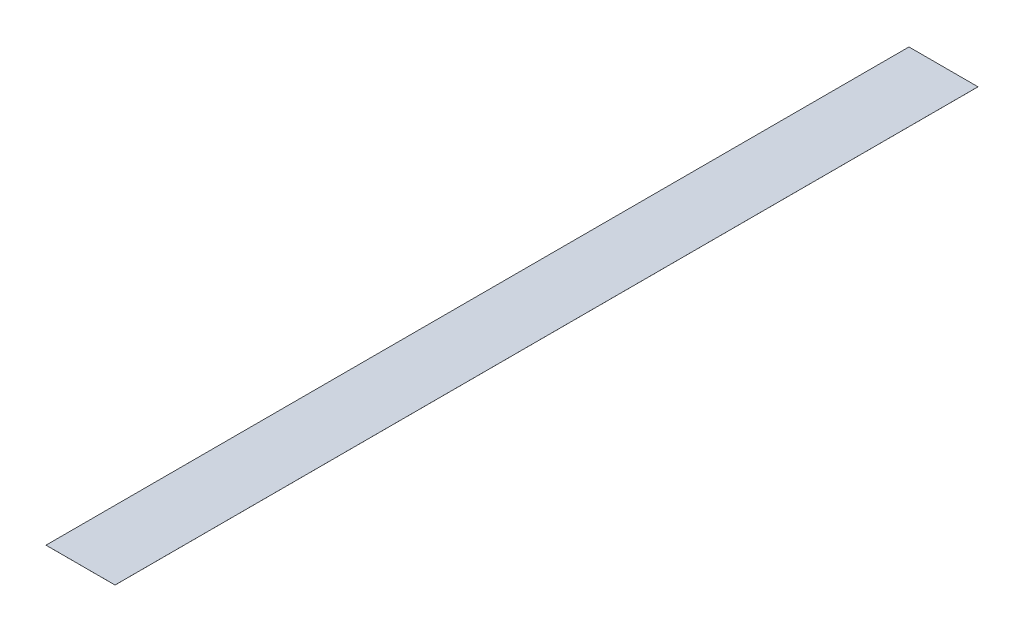
SolidWorks part; units mm, degrees
ref_plane "Plano frontal" through (0, 0, 0) normal (0, 0, 1) x (1, 0, 0)
ref_plane "Plano superior" through (0, 0, 0) normal (0, 1, 0) x (1, 0, 0)
ref_plane "Plano direito" through (0, 0, 0) normal (1, 0, 0) x (0, 0, -1)
sketch "Esboço1" plane through (0, 0, 0) normal (0, 1, 0) x (1, 0, 0)
  line L0 (-1093, 595.536) -> (-1073, 595.536)
  line L1 (0, 0) -> (18.9344, 0)
  line L2 (0, 0) -> (0, 766.8662)
  line L3 (0, 766.8662) -> (18.9344, 766.8662)
  line L4 (18.9344, 0) -> (18.9344, 766.8662)
  line L5 (-381.6968, 766.8662) -> (-362.7624, 766.8662)
  line L6 (-381.6968, 766.8662) -> (-381.6968, 345.536)
  line L7 (-381.6968, 345.536) -> (-362.7624, 345.536)
  line L8 (-362.7624, 766.8662) -> (-362.7624, 345.536)
  line L9 (-858.9344, 645.536) -> (-840, 645.536)
  line L10 (-858.9344, 645.536) -> (-858.9344, 345.536)
  line L11 (-858.9344, 345.536) -> (-840, 345.536)
  line L12 (-840, 645.536) -> (-840, 345.536)
  line L13 (-853.5858, 925.2213) -> (-1253.5858, 925.2213)
  line L14 (-853.5858, 925.2213) -> (-853.5858, 945.2213)
  line L15 (-853.5858, 945.2213) -> (-1253.5858, 945.2213)
  line L16 (-1253.5858, 925.2213) -> (-1253.5858, 945.2213)
  line L17 (-1093, 595.536) -> (-1093, 195.536)
  line L18 (-1093, 195.536) -> (-1073, 195.536)
  line L19 (-1073, 595.536) -> (-1073, 195.536)
  line L21 (-858.9344, 427.7897) -> (-1250.0103, 427.7897)
  line L23 (-858.9344, 407.7897) -> (-1250.0103, 407.7897)
  line L24 (-1250.0103, 427.7897) -> (-1250.0103, 407.7897)
  line L33 (-1439.6613, 239.7512) -> (-1560.0448, 239.7512)
  line L34 (-1439.6613, 239.7512) -> (-1439.6613, 219.7512)
  line L35 (-1439.6613, 219.7512) -> (-1560.0448, 219.7512)
  line L36 (-1560.0448, 239.7512) -> (-1560.0448, 219.7512)
  line L37 (-1627.2015, 576.144) -> (-1607.2015, 576.144)
  line L38 (-1627.2015, 576.144) -> (-1627.2015, 317.0654)
  line L39 (-1627.2015, 317.0654) -> (-1607.2015, 317.0654)
  line L40 (-1607.2015, 576.144) -> (-1607.2015, 317.0654)
  line L41 (-1627.2015, 769.6927) -> (-1607.2015, 769.6927)
  line L42 (-1627.2015, 769.6927) -> (-1627.2015, 1019.6927)
  line L43 (-1627.2015, 1019.6927) -> (-1607.2015, 1019.6927)
  line L44 (-1607.2015, 769.6927) -> (-1607.2015, 1019.6927)
  line L45 (-1691.6077, 639.3653) -> (-1671.6077, 639.3653)
  line L46 (-1691.6077, 639.3653) -> (-1691.6077, 889.3653)
  line L47 (-1691.6077, 889.3653) -> (-1671.6077, 889.3653)
  line L48 (-1671.6077, 639.3653) -> (-1671.6077, 889.3653)
  arc A6 (-381.6968, 766.8662) -> (18.9344, 766.8662) centre (-181.3812, 766.8662) cw
  arc A7 (-362.7624, 766.8662) -> (0, 766.8662) centre (-181.3812, 766.8662) cw
  arc A8 (-362.7624, 345.536) -> (-858.9344, 345.536) centre (-610.8484, 345.536) cw
  arc A9 (-381.6968, 345.536) -> (-840, 345.536) centre (-610.8484, 345.536) cw
  arc A10 (-840, 645.536) -> (-803.6955, 702.0415) centre (-777.8744, 645.536) cw
  arc A11 (-803.6955, 702.0415) -> (-853.5858, 945.2213) centre (-856.6336, 817.8884) ccw
  arc A12 (-858.9344, 645.536) -> (-814.4955, 717.9247) centre (-777.7563, 645.536) cw
  arc A13 (-814.4955, 717.9247) -> (-853.5858, 925.2213) centre (-864.2122, 815.8835) ccw
  arc A14 (-1093, 595.536) -> (-1188.5366, 677.9223) centre (-1176.2913, 595.536) ccw
  arc A15 (-1188.5366, 677.9223) -> (-1354.3411, 742.8189) centre (-1214.8489, 854.9525) cw
  arc A16 (-1354.3411, 742.8189) -> (-1253.5858, 945.2213) centre (-1257.3278, 820.805) cw
  arc A17 (-1073, 595.536) -> (-1188.5366, 698.0004) centre (-1176.2038, 595.536) ccw
  arc A18 (-1188.5366, 698.0004) -> (-1341.8208, 766.8662) centre (-1207.9995, 859.705) cw
  arc A19 (-1341.8208, 766.8662) -> (-1253.5858, 925.2213) centre (-1258.876, 824.4093) cw
  arc A22 (-1368.7558, 309.7722) -> (-1439.6613, 219.7512) centre (-1474.849, 320.402) cw
  arc A23 (-1388.5562, 309.7722) -> (-1439.6613, 239.7512) centre (-1477.6183, 321.1143) cw
  arc A24 (-1388.5562, 309.7722) -> (-1250.0103, 427.7897) centre (-1254.4723, 292.6965) cw
  arc A25 (-1607.2015, 317.0654) -> (-1560.0448, 239.7512) centre (-1520.2441, 317.0654) ccw
  arc A26 (-1627.2015, 317.0654) -> (-1560.0448, 219.7512) centre (-1523.1159, 317.0654) ccw
  arc A27 (-1368.7558, 309.7722) -> (-1250.0103, 407.7897) centre (-1259.9289, 298.8686) cw
extrude "Ressalto-extrusão18" add sketch "Esboço1" along normal blind 0.01 contours L46 L47 L48 L45
